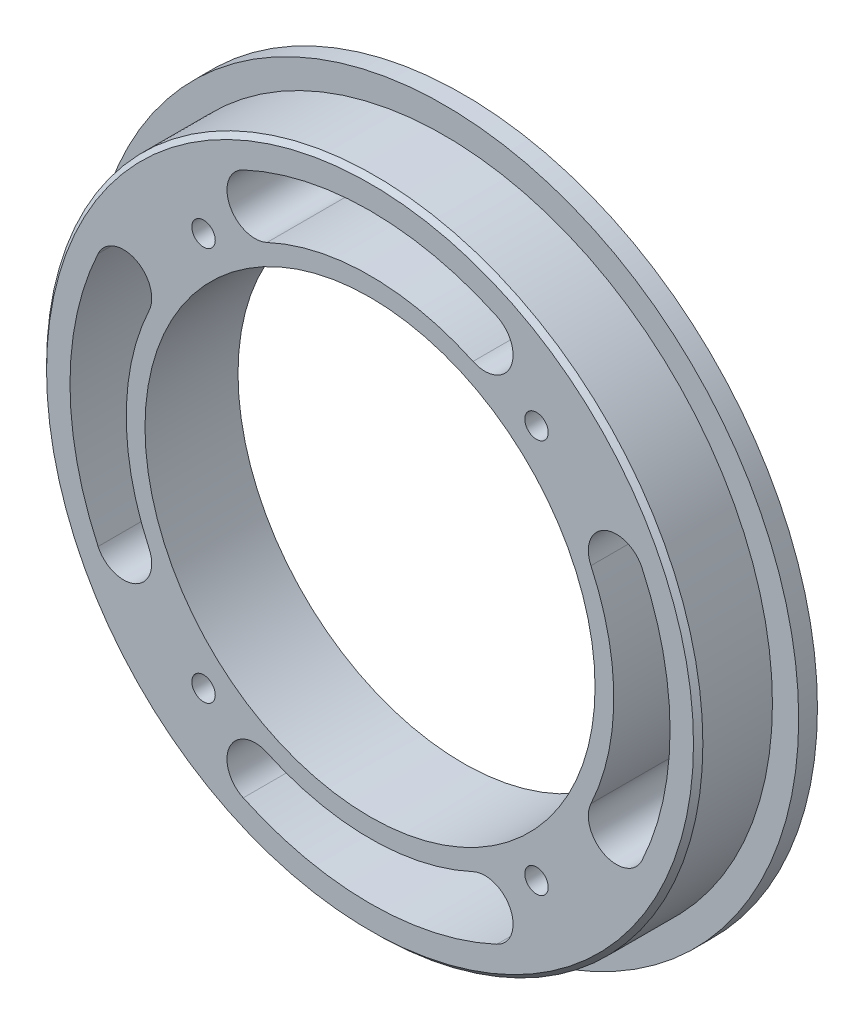
SolidWorks part; units mm, degrees
material "6061 合金"
ref_plane "前视基准面" through (0, 0, 0) normal (0, 0, 1) x (1, 0, 0)
ref_plane "上视基准面" through (0, 0, 0) normal (0, 1, 0) x (1, 0, 0)
ref_plane "右视基准面" through (0, 0, 0) normal (1, 0, 0) x (0, 0, -1)
sketch "草图1" plane through (0, 0, 0) normal (0, 0, 1) x (1, 0, 0)
  circle A0 centre (0, 0) radius 35
  circle A1 centre (0, 0) radius 24
  dimension "D1" = 70
  dimension "D2" = 48
extrude "凸台-拉伸1" add sketch "草图1" along normal blind 7.92
sketch "草图2" plane through (0, 0, 0) normal (0, 0, -1) x (-1, 0, 0)
  circle A1 centre (0, 0) radius 24 construction
  circle A2 centre (0, 0) radius 37.8
  circle A3 centre (0, 0) radius 37.8
  circle A4 centre (0, 0) radius 24
  dimension "D1" = 2.8
extrude "凸台-拉伸2" add sketch "草图2" along normal blind 2
sketch "草图3" plane through (0, 0, 7.92) normal (0, 0, 1) x (1, 0, 0)
  circle A0 centre (0, 0) radius 28 construction
  circle A1 centre (0, 0) radius 24 construction
  dimension "D1" = 4
sketch "草图4" plane through (0, 0, 7.92) normal (0, 0, 1) x (1, 0, 0)
  line L0 (0, 0) -> (27.5, 0) construction
  line L1 (-17.7553, 21) -> (17.7553, 21) construction
  line L2 (-17.7553, -21) -> (17.7553, -21) construction
  circle A0 centre (0, 0) radius 27.5 construction
  dimension "D1" = 55
  dimension "D2" = 21
  dimension "D3" = 21
hole_wizard "M3 螺纹孔1" positions "草图7" profile "草图8" tap size "M3" standard "GB" end condition through all
sketch "草图7" plane through (0, 0, 7.92) normal (0, 0, 1) x (1, 0, 0)
  point P0 (-17.7553, 21)
  point P3 (-17.7553, -21)
  point P6 (17.7553, -21)
  point P9 (17.7553, 21)
sketch "草图8" plane through (-17.7553, 21, 7.92) normal (1, 0, 0) x (0, -1, 0)
  line L0 (0, 0) -> (0, 9.92)
  line L1 (0, 9.92) -> (1.25, 9.92)
  line L2 (1.25, 9.92) -> (1.25, 0)
  line L5 (1.25, 0) -> (0, 0)
  line L11 (0, -6.35) -> (0, 107.95) construction
  dimension "通孔螺纹孔钻头直径" = 2.5
  dimension "通孔螺纹孔钻头深度" = 9.92
cosmetic thread "孔螺蚊线3" parameters "D2"=3
cosmetic thread "孔螺蚊线4" parameters "D2"=3
cosmetic thread "孔螺蚊线5" parameters "D2"=3
cosmetic thread "孔螺蚊线6" parameters "D2"=3
chamfer "倒角1" distance 0.5 angle 45 1 edges at (35, 0, 7.92)
sketch "草图9" plane through (0, 0, 7.92) normal (0, 0, 1) x (1, 0, 0)
  line L0 (29, 0) -> (0, 0) construction
  line L1 (0, 0) -> (26.2829, 12.2559) construction
  arc A0 (26.2829, -12.2559) -> (26.2829, 12.2559) centre (0, 0) ccw construction
  arc A1 (29.0018, -13.5238) -> (29.0018, 13.5238) centre (0, 0) ccw
  arc A2 (23.564, -10.9881) -> (23.564, 10.9881) centre (0, 0) ccw
  arc A3 (23.564, -10.9881) -> (29.0018, -13.5238) centre (26.2829, -12.2559) ccw
  arc A4 (29.0018, 13.5238) -> (23.564, 10.9881) centre (26.2829, 12.2559) ccw
  arc A5 (-12.2559, -26.2829) -> (12.2559, -26.2829) centre (0, 0) ccw construction
  arc A6 (-13.5238, -29.0018) -> (13.5238, -29.0018) centre (0, 0) ccw
  arc A7 (-10.9881, -23.564) -> (10.9881, -23.564) centre (0, 0) ccw
  arc A8 (-10.9881, -23.564) -> (-13.5238, -29.0018) centre (-12.2559, -26.2829) ccw
  arc A9 (13.5238, -29.0018) -> (10.9881, -23.564) centre (12.2559, -26.2829) ccw
  arc A10 (-26.2829, 12.2559) -> (-26.2829, -12.2559) centre (0, 0) ccw construction
  arc A11 (-29.0018, 13.5238) -> (-29.0018, -13.5238) centre (0, 0) ccw
  arc A12 (-23.564, 10.9881) -> (-23.564, -10.9881) centre (0, 0) ccw
  arc A13 (-23.564, 10.9881) -> (-29.0018, 13.5238) centre (-26.2829, 12.2559) ccw
  arc A14 (-29.0018, -13.5238) -> (-23.564, -10.9881) centre (-26.2829, -12.2559) ccw
  arc A15 (12.2559, 26.2829) -> (-12.2559, 26.2829) centre (0, 0) ccw construction
  arc A16 (13.5238, 29.0018) -> (-13.5238, 29.0018) centre (0, 0) ccw
  arc A17 (10.9881, 23.564) -> (-10.9881, 23.564) centre (0, 0) ccw
  arc A18 (10.9881, 23.564) -> (13.5238, 29.0018) centre (12.2559, 26.2829) ccw
  arc A19 (-13.5238, 29.0018) -> (-10.9881, 23.564) centre (-12.2559, 26.2829) ccw
  point P4 (29, 0)
  point P17 (0, -29)
  point P24 (-29, 0)
  point P31 (0, 29)
  point P36 (0, 0)
  dimension "D2" = 26
  dimension "D3" = 3
  dimension "D1" = 25
  dimension "D4" = 4
extrude "切除-拉伸1" cut sketch "草图9" against normal up to surface (9.92 mm away) up to face at (-24, 0, -2)
